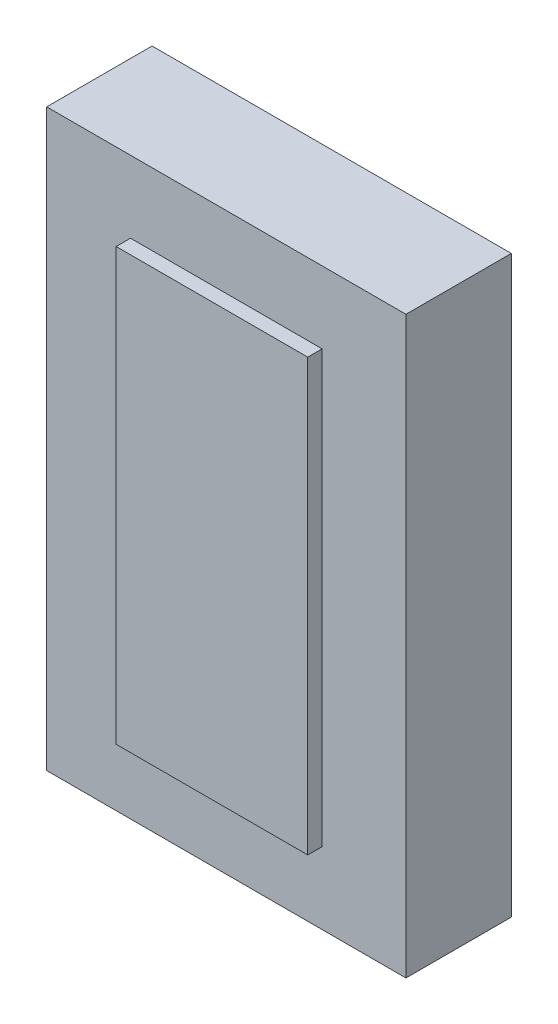
SolidWorks part; units mm, degrees
ref_plane "Front Plane" through (0, 0, 0) normal (0, 0, 1) x (1, 0, 0)
ref_plane "Top Plane" through (0, 0, 0) normal (0, 1, 0) x (1, 0, 0)
ref_plane "Right Plane" through (0, 0, 0) normal (1, 0, 0) x (0, 0, -1)
sketch "Sketch1" plane through (0, 0, 0) normal (0, 0, 1) x (1, 0, 0)
  line L0 (0, 60) -> (0, -60) construction
  line L5 (-37.5, 60) -> (37.5, 60)
  line L6 (-37.5, 60) -> (-37.5, -60)
  line L7 (-37.5, -60) -> (37.5, -60)
  line L8 (37.5, 60) -> (37.5, -60)
  line L9 (-37.5, 0) -> (37.5, 0) construction
  dimension "D3" = 75
  dimension "D4" = 120
extrude "Boss-Extrude1" add sketch "Sketch1" along normal blind 22
sketch "Sketch3" plane through (0, 0, 0) normal (0, 0, 1) x (1, 0, 0)
  line L0 (-20, 45) -> (20, 45)
  line L1 (-20, 45) -> (-20, -45)
  line L2 (-20, -45) -> (20, -45)
  line L3 (20, 45) -> (20, -45)
  line L4 (0, 45) -> (0, -45) construction
  line L5 (-20, 0) -> (20, 0) construction
  dimension "D1" = 90
  dimension "D2" = 40
extrude "Boss-Extrude2" add sketch "Sketch3" along normal blind 25
